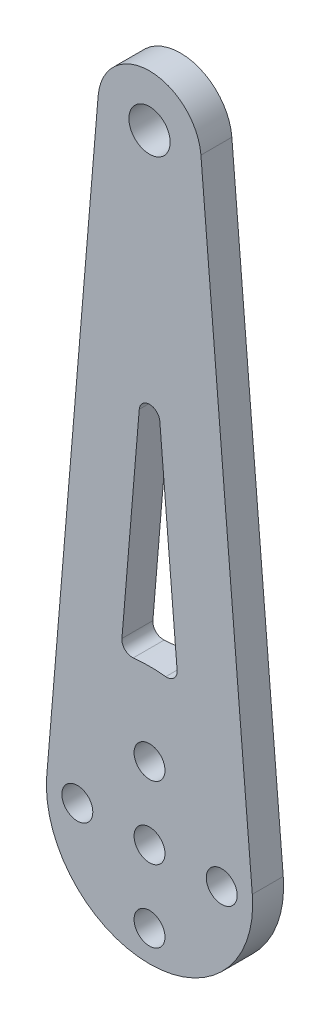
SolidWorks part; units mm, degrees
material "Thornel Mat VMA"
ref_plane "前视基准面" through (0, 0, 0) normal (0, 0, 1) x (1, 0, 0)
ref_plane "上视基准面" through (0, 0, 0) normal (0, 1, 0) x (1, 0, 0)
ref_plane "右视基准面" through (0, 0, 0) normal (1, 0, 0) x (0, 0, -1)
sketch "草图1" plane through (0, 0, 0) normal (0, 0, 1) x (1, 0, 0)
  line L0 (0, 0) -> (0, 60)
  line L2 (0, 0.25) -> (-136.5, 0.25) construction
  line L5 (-45.3314, 0.25) -> (33.243, 103.8167)
  dimension "D1" = 130
  dimension "D2" = 136.5
  dimension "D3" = 60
  dimension "D5" = 55
  dimension "D6" = 0.25
sketch "草图2" plane through (0, 0, 0) normal (0, 0, 1) x (1, 0, 0)
  line L0 (-9.9652, 0.8333) -> (-4.9826, 60.4167)
  line L1 (4.9826, 60.4167) -> (9.9652, 0.8333)
  circle A0 centre (0, 0) radius 1.5
  circle A1 centre (0, 0) radius 7 construction
  arc A2 (-9.9652, 0.8333) -> (9.9652, 0.8333) centre (0, 0) ccw
  circle A3 centre (0, 7) radius 1.5
  circle A4 centre (7, 0) radius 1.5
  circle A5 centre (0, -7) radius 1.5
  circle A6 centre (-7, 0) radius 1.5
  circle A7 centre (0, 60) radius 2
  arc A8 (4.9826, 60.4167) -> (-4.9826, 60.4167) centre (0, 60) ccw
  dimension "D1" = 3
  dimension "D2" = 14
  dimension "D3" = 20
  dimension "D4" = 3
  dimension "D6" = 4
  dimension "D7" = 5
  dimension "D5" = 4
extrude "凸台-拉伸1" add sketch "草图2" along normal blind 3
sketch "草图3" plane through (0, 0, 3) normal (0, 0, 1) x (1, 0, 0)
  line L2 (-4.9826, 60.4167) -> (-9.9652, 0.8333) construction
  line L3 (2.6764, 15.9949) -> (0.9965, 36.0833)
  line L4 (9.9652, 0.8333) -> (4.9826, 60.4167) construction
  line L7 (-0.9965, 36.0833) -> (-2.6764, 15.9949)
  arc A2 (1.5749, 14.9171) -> (-1.5749, 14.9171) centre (0, 0) ccw
  arc A4 (-9.9652, 0.8333) -> (9.9652, 0.8333) centre (0, 0) ccw construction
  circle A5 centre (0, 0) radius 10 construction
  arc A7 (-0.9965, 36.0833) -> (0.9965, 36.0833) centre (0, 36) cw
  arc A8 (1.5749, 14.9171) -> (2.6764, 15.9949) centre (1.6799, 15.9116) ccw
  arc A9 (-1.5749, 14.9171) -> (-2.6764, 15.9949) centre (-1.6799, 15.9116) cw
  point P14 (0, 60)
  dimension "D1" = 5
  dimension "D4" = 1
  dimension "D5" = 1
  dimension "D2" = 6
  dimension "D3" = 6
extrude "切除-拉伸1" cut sketch "草图3" against normal through all
